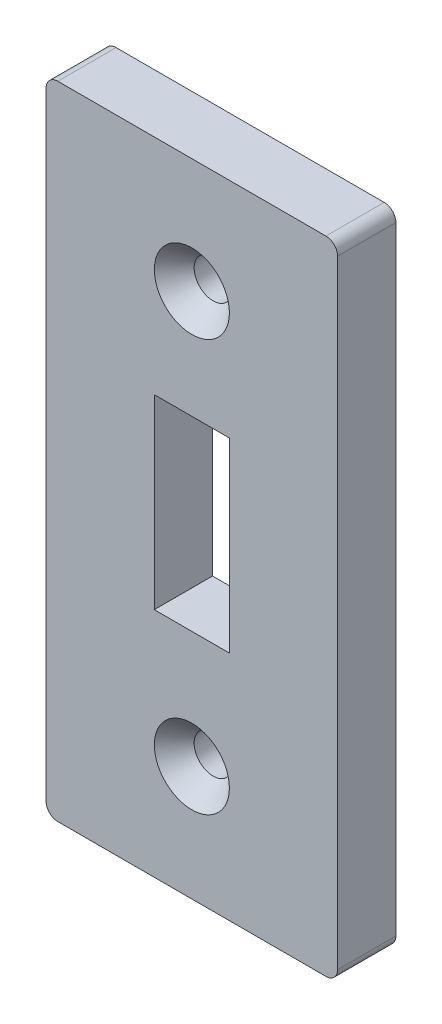
SolidWorks part; units mm, degrees
ref_plane "Front Plane" through (0, 0, 0) normal (0, 0, 1) x (1, 0, 0)
ref_plane "Top Plane" through (0, 0, 0) normal (0, 1, 0) x (1, 0, 0)
ref_plane "Right Plane" through (0, 0, 0) normal (1, 0, 0) x (0, 0, -1)
sketch "Sketch1" plane through (0, 0, 0) normal (0, 0, 1) x (1, 0, 0)
  line L0 (0.5425, -55.2713) -> (0.5425, -35.5813) construction
  line L1 (-24.4575, 54.7287) -> (25.5425, 54.7287)
  line L2 (-24.4575, 54.7287) -> (-24.4575, -55.2713)
  line L3 (-24.4575, -55.2713) -> (25.5425, -55.2713)
  line L4 (25.5425, 54.7287) -> (25.5425, -55.2713)
  line L5 (0.5425, 54.7287) -> (0.5425, -55.2713) construction
  line L6 (0.5425, 16.4434) -> (6.9925, 16.4434)
  line L7 (6.9925, 16.4434) -> (6.9925, -15.5066)
  line L8 (6.9925, -15.5066) -> (0.5425, -15.5066)
  line L9 (0.5425, -15.5066) -> (-5.9075, -15.5066)
  line L10 (-5.9075, -15.5066) -> (-5.9075, 16.4434)
  line L11 (-5.9075, 16.4434) -> (0.5425, 16.4434)
  line L12 (0.5425, 54.7287) -> (0.5425, 35.0387) construction
  dimension "D1" = 110
  dimension "D2" = 31.95
  dimension "D3" = 12.9
  dimension "D4" = 19.69
  dimension "D5" = 19.69
  dimension "D6" = 50
extrude "Boss-Extrude1" add sketch "Sketch1" along normal blind 10
sketch "Sketch2" plane through (0, 0, 10) normal (0, 0, 1) x (1, 0, 0)
  line L0 (0.5425, -55.2713) -> (0.5425, -35.5813)
  line L1 (-24.4575, -55.2713) -> (25.5425, -55.2713) construction
  line L2 (25.5425, 54.7287) -> (-24.4575, 54.7287) construction
  line L3 (0.5425, 54.7287) -> (0.5425, 35.0387)
  dimension "D1" = 19.69
  dimension "D2" = 19.69
hole_wizard "CSK for 1/4 Flat Head Machine Screw1" positions "Sketch3" profile "Sketch4" countersink size "1/4" standard "ANSI Inch" end condition through all
sketch "Sketch3" plane through (0, 0, 10) normal (0, 0, 1) x (1, 0, 0)
  point P0 (0.5425, -35.5813)
  point P3 (0.5425, 35.0387)
sketch "Sketch4" plane through (0.5425, -35.5813, 10) normal (1, 0, 0) x (0, -1, 0)
  line L0 (0, 0) -> (0, 10)
  line L1 (0, 10) -> (3.2639, 10)
  line L2 (3.2639, 10) -> (3.2639, 3.6524)
  line L3 (3.2639, 3.6524) -> (6.4389, 0)
  line L5 (6.4389, 0) -> (0, 0)
  line L6 (-3.2639, 3.6524) -> (-6.4389, 0) construction
  line L11 (0, -6.35) -> (0, 107.95) construction
  dimension "Thru Hole Dia." = 6.5278
  dimension "Thru Hole Depth" = 10
  dimension "Near C'Sink Dia." = 12.8778
  dimension "Near C'Sink Angle" = 82
fillet "Fillet1" radius 2 4 edges at (25.5425, 54.7287, 5) (25.5425, -55.2713, 5) (-24.4575, 54.7287, 5) (-24.4575, -55.2713, 5)
